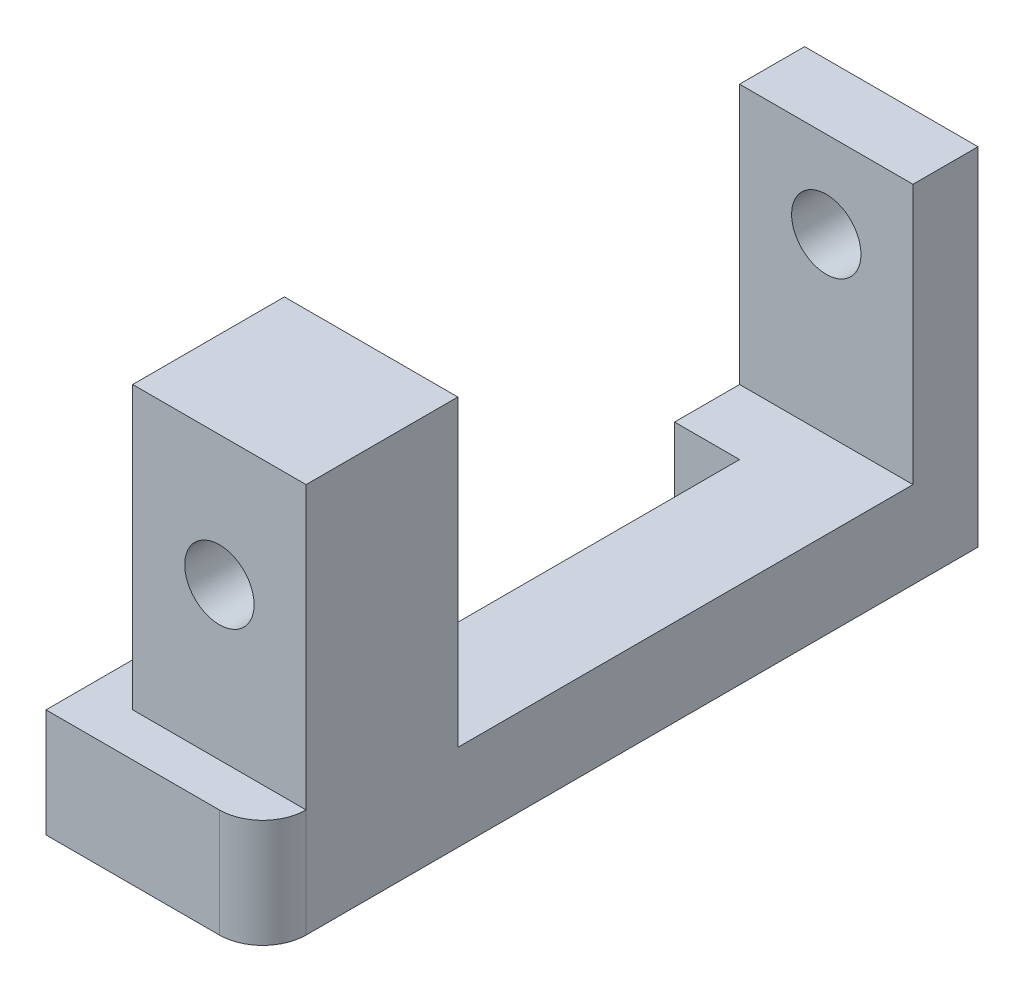
SolidWorks part; units mm, degrees
ref_plane "Front Plane" through (0, 0, 0) normal (0, 0, 1) x (1, 0, 0)
ref_plane "Top Plane" through (0, 0, 0) normal (0, 1, 0) x (1, 0, 0)
ref_plane "Right Plane" through (0, 0, 0) normal (1, 0, 0) x (0, 0, -1)
sketch "Sketch1" plane through (0, 0, 0) normal (1, 0, 0) x (0, 0, -1)
  line L0 (0, 0) -> (0, 16)
  line L1 (0, 16) -> (-3, 16)
  line L2 (-3, 16) -> (-3, 4)
  line L3 (-3, 4) -> (-24, 4)
  line L4 (-24, 4) -> (-24, 18)
  line L5 (-24, 18) -> (-31, 18)
  line L6 (-31, 18) -> (-31, 0)
  line L7 (-31, 0) -> (0, 0)
  dimension "D1" = 3
  dimension "D2" = 16
  dimension "D3" = 12
  dimension "D4" = 18
  dimension "D5" = 31
  dimension "D6" = 7
extrude "Boss-Extrude1" add sketch "Sketch1" against normal blind 8
sketch "Sketch3" plane through (-8, 0, 0) normal (-1, 0, 0) x (0, 0, 1)
  line L0 (3, 16) -> (3, 4) construction
  line L1 (3, 4) -> (24, 4)
  line L2 (3, 4) -> (3, 0)
  line L3 (3, 0) -> (24, 0)
  line L4 (24, 4) -> (24, 0)
  line L5 (24, 4) -> (24, 18) construction
  line L6 (31, 0) -> (0, 0) construction
  line L7 (3, 4) -> (24, 4) construction
extrude "Cut-Extrude1" [suppressed] cut sketch "Sketch3" against normal blind 4
sketch "Sketch5" plane through (0, 0, 3) normal (0, 0, 1) x (1, 0, 0)
  line L0 (-8, 0) -> (-3, 0)
  line L1 (-8, 0) -> (0, 0) construction
  line L2 (-3, 0) -> (-5, 4)
  line L3 (-5, 4) -> (-8, 4)
  line L4 (-8, 18) -> (-8, 0) construction
  line L5 (-8, 4) -> (-8, 0)
  dimension "D1" = 5
  dimension "D2" = 3
  dimension "D3" = 4
extrude "Cut-Extrude2" cut sketch "Sketch5" along normal up to surface (21 mm away) up to face at (-4, 11, 24)
sketch "Sketch6" plane through (0, 0, 31) normal (0, 0, 1) x (1, 0, 0)
  line L0 (0, 18) -> (0, 0) construction
  line L1 (-8, 0) -> (0, 0) construction
  circle A0 centre (-4, 12) radius 1.6
  dimension "D1" = 3.2
  dimension "D2" = 4
  dimension "D3" = 12
sketch "Sketch8" plane through (0, 0, 3) normal (0, 0, 1) x (1, 0, 0)
  line L0 (-8, 4) -> (-5, 4)
  line L1 (-5, 4) -> (-3, 0)
  line L2 (-3, 0) -> (-8, 0)
  line L3 (-8, 0) -> (-8, 4)
extrude "Boss-Extrude2" add sketch "Sketch8" along normal blind 3
sketch "Sketch11" plane through (0, 0, 0) normal (0, -1, 0) x (1, 0, 0)
  line L0 (-3, 24) -> (-8, 24) construction
  line L2 (-10, 26) -> (-10, 33)
  line L3 (-10, 33) -> (-2, 33)
  line L4 (0, 31) -> (-8, 31)
  line L5 (-8, 31) -> (-8, 24)
  line L6 (-8, 31) -> (0, 31) construction
  line L7 (0, 31) -> (0, 0) construction
  arc A0 (-2, 33) -> (0, 31) centre (-2, 31) cw
  arc A1 (-10, 26) -> (-8, 24) centre (-8, 26) ccw
  dimension "D1" = 2
  dimension "D2" = 2
extrude "Boss-Extrude5" add sketch "Sketch11" against normal blind 5
extrude "Cut-Extrude3" cut sketch "Sketch6" against normal through all
